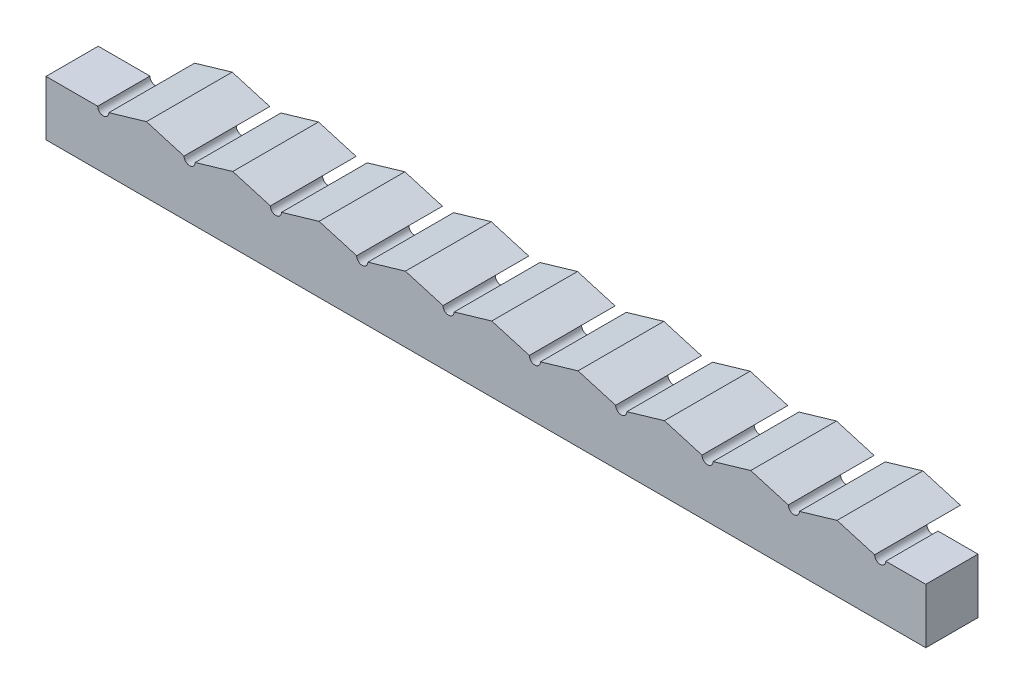
SolidWorks part; units mm, degrees
ref_plane "Front Plane" through (0, 0, 0) normal (0, 0, 1) x (1, 0, 0)
ref_plane "Top Plane" through (0, 0, 0) normal (0, 1, 0) x (1, 0, 0)
ref_plane "Right Plane" through (0, 0, 0) normal (1, 0, 0) x (0, 0, -1)
sketch "Sketch1" plane through (0, 0, 0) normal (0, 0, 1) x (1, 0, 0)
  line L1 (0, 0) -> (-406.4, 0)
  line L2 (0, 0) -> (0, -25.4)
  line L3 (0, -25.4) -> (-406.4, -25.4)
  line L4 (-406.4, 0) -> (-406.4, -25.4)
  dimension "D1" = 25.4
  dimension "D2" = 406.4
extrude "Boss-Extrude1" add sketch "Sketch1" along normal blind 24.13
sketch "Sketch3" plane through (0, 0, 24.13) normal (0, 0, 1) x (1, 0, 0)
  line L0 (0, 0) -> (-406.4, 0) construction
  circle A0 centre (-379.9498, 0) radius 2.5717
  circle A1 centre (-340.0718, 0) radius 2.5717
  circle A2 centre (-300.1938, 0) radius 2.5717
  circle A3 centre (-260.3158, 0) radius 2.5717
  circle A4 centre (-220.4378, 0) radius 2.5717
  circle A5 centre (-180.5598, 0) radius 2.5717
  circle A6 centre (-140.6818, 0) radius 2.5717
  circle A7 centre (-100.8038, 0) radius 2.5717
  circle A8 centre (-60.9258, 0) radius 2.5717
  circle A9 centre (-21.0478, 0) radius 2.5717
  dimension "D1" = 5.1435
  dimension "D2" = 10
extrude "Cut-Extrude1" cut sketch "Sketch3" against normal blind 39.624
sketch "Sketch4" plane through (0, 0, 24.13) normal (0, 0, 1) x (1, 0, 0)
  line L0 (-377.378, 0) -> (-360.0108, 5.08)
  line L1 (-360.0108, 5.08) -> (-342.6435, 0)
  line L2 (-342.6435, 0) -> (-377.378, 0)
  line L3 (-337.5, 0) -> (-320.1328, 5.08)
  line L4 (-302.7655, 0) -> (-337.5, 0)
  line L5 (-320.1328, 5.08) -> (-302.7655, 0)
  line L6 (-297.622, 0) -> (-280.2548, 5.08)
  line L7 (-262.8875, 0) -> (-297.622, 0)
  line L8 (-280.2548, 5.08) -> (-262.8875, 0)
  line L9 (-257.744, 0) -> (-240.3768, 5.08)
  line L10 (-223.0095, 0) -> (-257.744, 0)
  line L11 (-240.3768, 5.08) -> (-223.0095, 0)
  line L12 (-217.866, 0) -> (-200.4988, 5.08)
  line L13 (-183.1315, 0) -> (-217.866, 0)
  line L14 (-200.4988, 5.08) -> (-183.1315, 0)
  line L15 (-177.988, 0) -> (-160.6208, 5.08)
  line L16 (-143.2535, 0) -> (-177.988, 0)
  line L17 (-160.6208, 5.08) -> (-143.2535, 0)
  line L18 (-138.11, 0) -> (-120.7428, 5.08)
  line L19 (-103.3755, 0) -> (-138.11, 0)
  line L20 (-120.7428, 5.08) -> (-103.3755, 0)
  line L21 (-98.232, 0) -> (-80.8648, 5.08)
  line L22 (-63.4975, 0) -> (-98.232, 0)
  line L23 (-80.8648, 5.08) -> (-63.4975, 0)
  line L24 (-58.354, 0) -> (-40.9868, 5.08)
  line L25 (-23.6195, 0) -> (-58.354, 0)
  line L26 (-40.9868, 5.08) -> (-23.6195, 0)
  dimension "D1" = 5.08
  dimension "D2" = 9
extrude "Boss-Extrude2" add sketch "Sketch4" against normal blind 39.624
